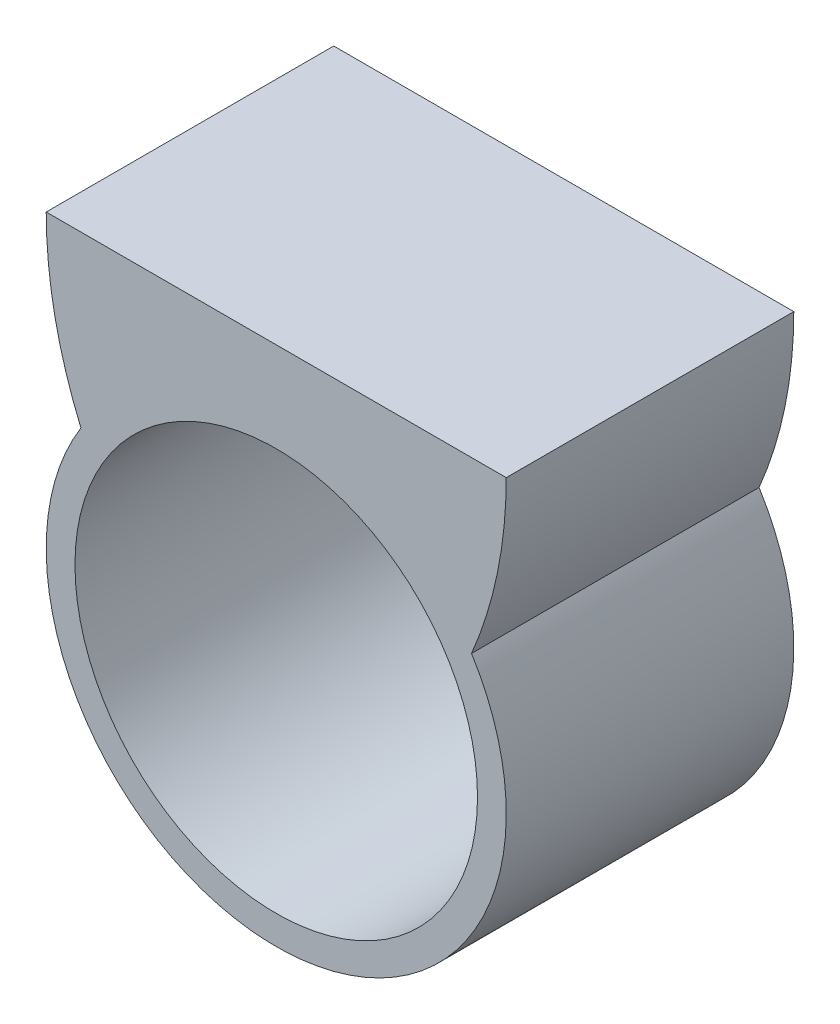
SolidWorks part; units mm, degrees
ref_plane "Front Plane" through (0, 0, 0) normal (0, 0, 1) x (1, 0, 0)
ref_plane "Top Plane" through (0, 0, 0) normal (0, 1, 0) x (1, 0, 0)
ref_plane "Right Plane" through (0, 0, 0) normal (1, 0, 0) x (0, 0, -1)
sketch "Sketch1" plane through (0, 0, 0) normal (0, 0, 1) x (1, 0, 0)
  circle A0 centre (0, 0) radius 40
  circle A1 centre (0, 0) radius 35
  dimension "D1" = 80
  dimension "D2" = 5
extrude "Boss-Extrude1" add sketch "Sketch1" along normal blind 50
sketch "Sketch2" plane through (0, 0, 50) normal (0, 0, 1) x (1, 0, 0)
  line L1 (40, 50.6359) -> (-40, 50.6359)
  line L2 (0, 50.6359) -> (0, 35)
  arc A0 (33.9586, 21.138) -> (-33.9586, 21.138) centre (0, 0) ccw
  arc A5 (-40, 50.6359) -> (-33.9586, 21.138) centre (35.0344, 50.6359) ccw
  circle A6 centre (0, 0) radius 40 construction
  circle A7 centre (0, 0) radius 35 construction
  arc A8 (40, 50.6359) -> (33.9586, 21.138) centre (-35.0344, 50.6359) cw
  circle M9 centre (0, 0) radius 40
extrude "Boss-Extrude2" add sketch "Sketch2" against normal blind 50 contours L1 A5 L2 M9 | A8 L1 L2 M9
scale "Scale1" bodies to scale 102 scale about centroid uniform scaling yes scale factor 1.5
